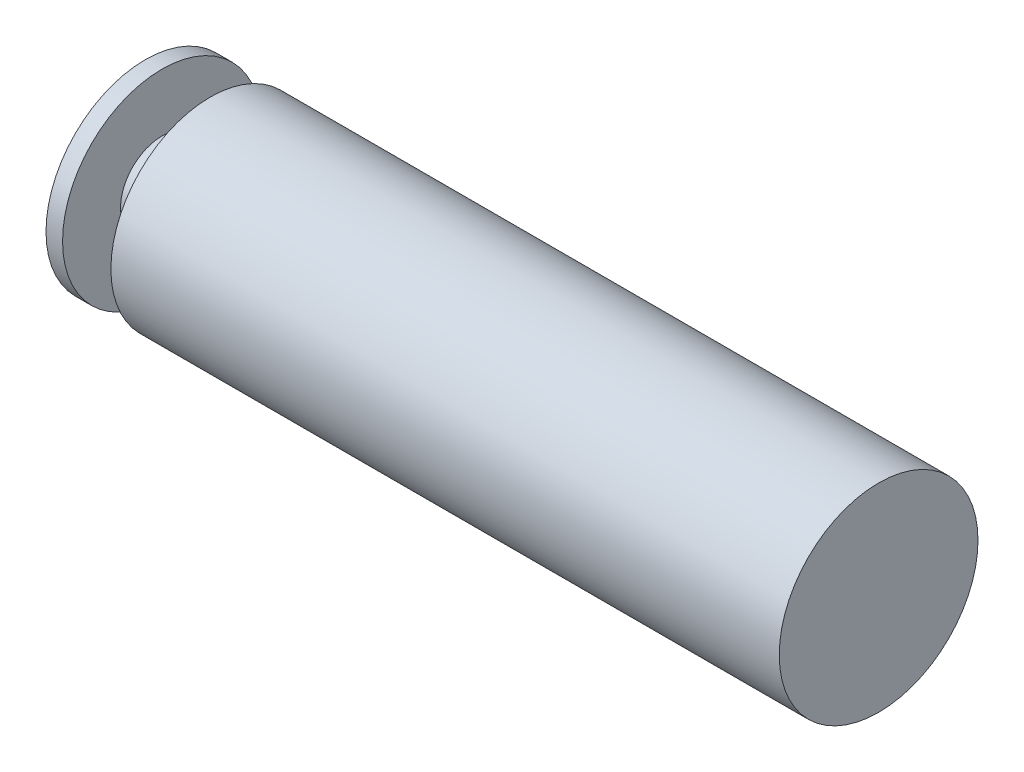
SolidWorks part; units mm, degrees
ref_plane "Front Plane" through (0, 0, 0) normal (0, 0, 1) x (1, 0, 0)
ref_plane "Top Plane" through (0, 0, 0) normal (0, 1, 0) x (1, 0, 0)
ref_plane "Right Plane" through (0, 0, 0) normal (1, 0, 0) x (0, 0, -1)
sketch "Sketch1" plane through (0, 0, 0) normal (0, 0, 1) x (1, 0, 0)
  line L0 (0, 0) -> (0, 12)
  line L1 (0, 12) -> (2, 12)
  line L2 (2, 12) -> (2, 5)
  line L3 (2, 5) -> (7.8346, 5)
  line L4 (7.8346, 5) -> (7.8346, 12)
  line L5 (7.8346, 12) -> (88.5466, 12)
  line L6 (88.5466, 12) -> (88.5466, 0)
  line L7 (88.5466, 0) -> (0, 0)
  dimension "D1" = 12
  dimension "D2" = 2
  dimension "D3" = 7
  dimension "D4" = 7
revolve "Revolve1" add sketch "Sketch1" angle 360 about L7
